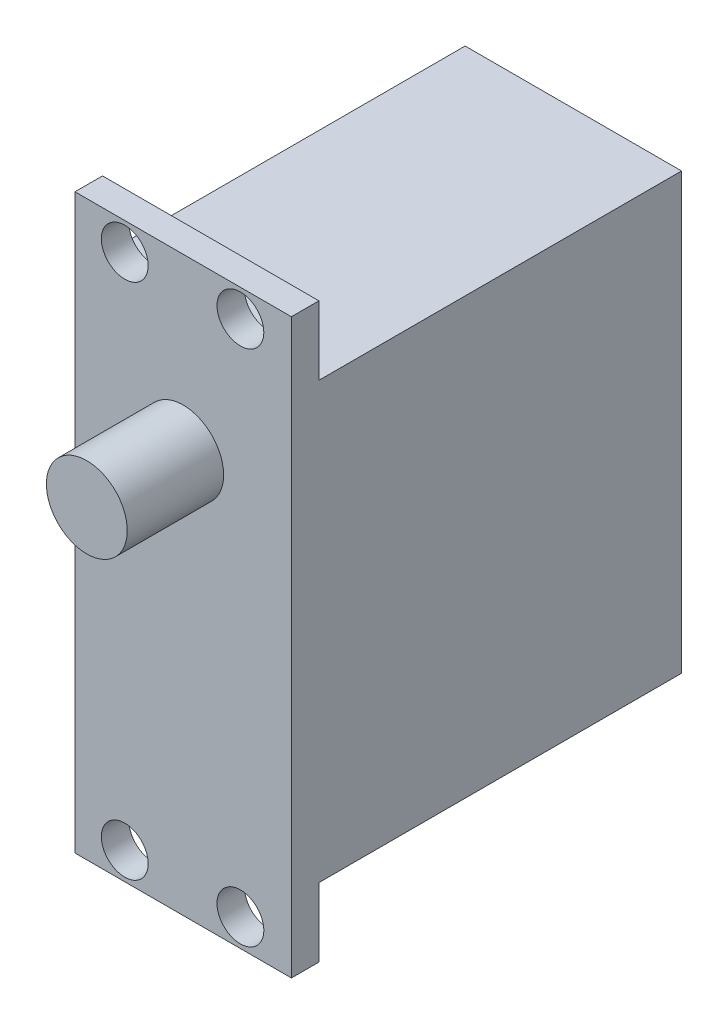
SolidWorks part; units mm, degrees
ref_plane "Front Plane" through (0, 0, 0) normal (0, 0, 1) x (1, 0, 0)
ref_plane "Top Plane" through (0, 0, 0) normal (0, 1, 0) x (1, 0, 0)
ref_plane "Right Plane" through (0, 0, 0) normal (1, 0, 0) x (0, 0, -1)
sketch "Sketch1" plane through (0, 0, 0) normal (1, 0, 0) x (0, 0, -1)
  line L0 (-54.9163, -3.1297) -> (-54.9163, 37.0023)
  line L1 (-54.9163, 37.0023) -> (-18.9245, 37.0023)
  line L2 (-18.9245, 37.0023) -> (-18.9245, -3.1297)
  line L3 (-54.9163, -3.1297) -> (-18.9245, -3.1297)
  dimension "D1" = 40.132
  dimension "D2" = 35.9918
extrude "Extrude1" add sketch "Sketch1" along normal mid plane 19.9644
sketch "Sketch2" plane through (0, 0, 54.9163) normal (0, 0, 1) x (1, 0, 0)
  line L0 (0, 37.0023) -> (0, -3.1297) construction
  line L1 (9.9822, 37.0023) -> (-9.9822, 37.0023) construction
  line L2 (9.9822, -3.1297) -> (-9.9822, -3.1297) construction
  line L3 (-9.9822, 27.5789) -> (9.9822, 27.5789) construction
  line L4 (-9.9822, 37.0023) -> (-9.9822, -3.1297) construction
  line L5 (9.9822, 37.0023) -> (9.9822, -3.1297) construction
  circle A0 centre (0, 27.5789) radius 3.7305
  dimension "D1" = 9.4234
extrude "Extrude2" add sketch "Sketch2" along normal blind 8.89 separate body
sketch "Sketch5" plane through (0, 0, 54.9163) normal (0, 0, 1) x (1, 0, 0)
  line L0 (-9.9822, 37.0023) -> (-9.9822, -3.1297) construction
  line L1 (-9.9822, 37.0023) -> (9.9822, 37.0023)
  line L2 (-9.9822, 37.0023) -> (-9.9822, 43.3523)
  line L3 (-9.9822, 43.3523) -> (9.9822, 43.3523)
  line L4 (9.9822, 37.0023) -> (9.9822, 43.3523)
  line L5 (-9.9822, 16.9363) -> (18.6904, 16.9363) construction
  line L6 (0, 16.9363) -> (0, 47.5435) construction
  line L7 (-15.5344, 40.8218) -> (9.9822, 40.8218) construction
  line L8 (9.9822, -3.1297) -> (9.9822, -9.4797)
  line L9 (-9.9822, -9.4797) -> (9.9822, -9.4797)
  line L10 (-9.9822, -3.1297) -> (-9.9822, -9.4797)
  line L11 (-9.9822, -3.1297) -> (9.9822, -3.1297)
  circle A0 centre (5.2781, 40.8218) radius 2.159
  circle A1 centre (-5.3899, 40.8218) radius 2.159
  circle A2 centre (-5.3899, -6.9492) radius 2.159
  circle A3 centre (5.2781, -6.9492) radius 2.159
  point P27 (0, 0)
  dimension "D1" = 4.318
  dimension "D2" = 10.668
  dimension "D3" = 6.35
extrude "Extrude5" add sketch "Sketch5" against normal blind 2.54
